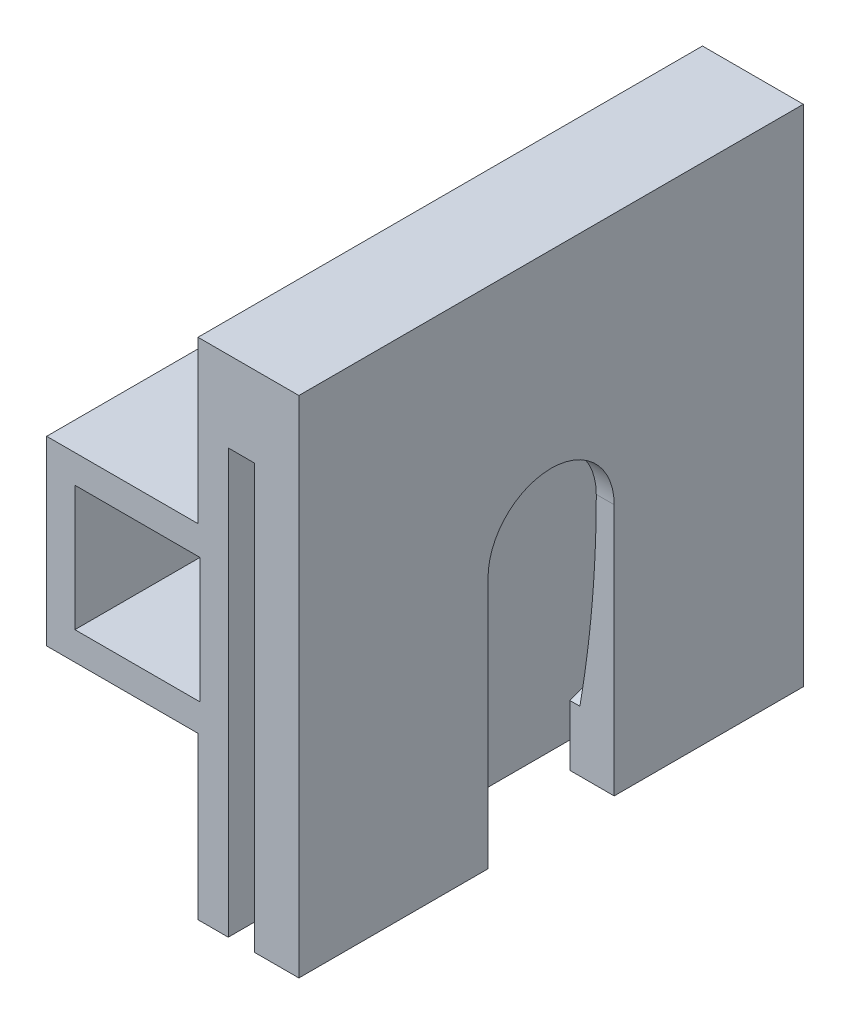
SolidWorks part; units mm, degrees
ref_plane "Plan de face" through (0, 0, 0) normal (0, 0, 1) x (1, 0, 0)
ref_plane "Plan de dessus" through (0, 0, 0) normal (0, 1, 0) x (1, 0, 0)
ref_plane "Plan de droite" through (0, 0, 0) normal (1, 0, 0) x (0, 0, -1)
sketch "Sketch1" plane through (0, 0, 0) normal (0, 0, 1) x (1, 0, 0)
  line L1 (4.5, 4.5) -> (-4.5, 4.5)
  line L2 (4.5, 4.5) -> (4.5, -4.5)
  line L3 (4.5, -4.5) -> (-4.5, -4.5)
  line L4 (-4.5, 4.5) -> (-4.5, -4.5)
  line L5 (4.5, 4.5) -> (-4.5, -4.5) construction
  line L6 (4.5, -4.5) -> (-4.5, 4.5) construction
  point P0 (0, 0)
  dimension "D1" = 9
extrude "Boss-Extrude1" add sketch "Sketch1" along normal blind 25
sketch "Sketch2" plane through (0, 0, 0) normal (0, 0, -1) x (-1, 0, 0)
  line L1 (3, 3) -> (-3, 3)
  line L2 (3, 3) -> (3, -3)
  line L3 (3, -3) -> (-3, -3)
  line L4 (-3, 3) -> (-3, -3)
  line L5 (3, 3) -> (-3, -3) construction
  line L6 (3, -3) -> (-3, 3) construction
  point P0 (0, 0)
  dimension "D1" = 6
extrude "Cut-Extrude1" cut sketch "Sketch2" against normal through all
sketch "Sketch4" plane through (4.5, 0, 0) normal (1, 0, 0) x (0, 0, -1)
  line L0 (-25, -4.5) -> (-25, 4.5) construction
  line L1 (-25, 12.5) -> (0, 12.5)
  line L2 (-25, 12.5) -> (-25, -12.5)
  line L3 (-25, -12.5) -> (0, -12.5)
  line L4 (0, 12.5) -> (0, -12.5)
  line L5 (0, -4.5) -> (0, 4.5) construction
  line L6 (-25, 12.5) -> (0, 4.5) construction
  line L7 (0, -4.5) -> (-25, -12.5) construction
extrude "Boss-Extrude2" add sketch "Sketch4" against normal up to surface (1.5 mm away) up to face at (3, 0, 12.5)
ref_plane "Plane1" through (4.5, 0, 0) normal (1, 0, 0) x (0, 0, -1)
ref_plane "Plane2" through (0, 0, 12.5) normal (0, 0, -1) x (-1, 0, 0)
ref_plane "Plane3" through (0, 0, 0) normal (0, 1, 0) x (1, 0, 0)
ref_axis "Axis1" through (4.575, 0, 12.5) along (-1, 0, 0)
sketch "Sketch5" plane through (4.5, 0, 0) normal (1, 0, 0) x (0, 0, -1)
  line L4 (0, -12.5) -> (0, 12.5)
  line L5 (0, 12.5) -> (-25, 12.5)
  line L6 (-25, 12.5) -> (-25, -12.5)
  line L7 (-25, -12.5) -> (0, -12.5)
  line L8 (0, -12.5) -> (0, 12.5)
  line L9 (0, 12.5) -> (-25, 12.5)
  line L10 (-25, 12.5) -> (-25, -12.5)
  line L11 (-25, -12.5) -> (0, -12.5)
  dimension "D1" = 0
extrude "Boss-Extrude3" add sketch "Sketch5" along normal blind 3.5
sketch "Sketch6" plane through (0, 0, 12.5) normal (0, 0, -1) x (-1, 0, 0)
  line L0 (-4.5, 10) -> (-4.5, 0)
  line L1 (-4.5, 13.75) -> (-4.5, -13.75) construction
  line L2 (-4.5, 10) -> (-6.3, 10)
  line L3 (-6.3, 10) -> (-6.3, 0) construction
  line L4 (0.825, 0) -> (-0.825, 0) construction
  line L5 (-8, 12.5) -> (-8, -12.5) construction
  line L6 (-8, 12.5) -> (-8, -12.5) construction
  line L7 (-8, 12.5) -> (-6.3, 10) construction
  line L9 (-4.5, 0) -> (-7.1999, 0)
  arc A0 (-6.3, 10) -> (-7.1999, 0) centre (48.81, 0) ccw
  dimension "D3" = 55.11
  dimension "D1" = 1.8
  dimension "D2" = 10
revolve "Cut-Revolve2" cut sketch "Sketch6" angle 360 about axis through (4.575, 0, 12.5) along (-1, 0, 0)
sketch "Sketch7" plane through (0, -12.5, 0) normal (0, -1, 0) x (1, 0, 0)
  line L0 (3, 25) -> (8, 25) construction
  line L1 (4.5, 25) -> (6.3, 25)
  line L2 (4.5, 25) -> (4.5, 0)
  line L3 (4.5, 0) -> (6.3, 0)
  line L4 (6.3, 25) -> (6.3, 0)
  line L5 (3, 0) -> (8, 0) construction
  line L6 (4.5, 2.5) -> (4.5, 22.5) construction
  line L7 (6.3, 2.5) -> (6.3, 22.5) construction
extrude "Cut-Extrude5" cut sketch "Sketch7" against normal blind 21
sketch "Sketch8" plane through (8, 0, 0) normal (1, 0, 0) x (0, 0, -1)
  line L0 (-12.5, 0) -> (-12.5, -12.5) construction
  line L1 (-9.375, 0) -> (-9.375, -12.5)
  line L2 (-15.625, 0) -> (-15.625, -12.5)
  line L3 (-12.5, -4.95) -> (-12.5, 4.95) construction
  line L4 (0.825, 0) -> (-0.825, 0) construction
  line L5 (-25, -12.5) -> (0, -12.5) construction
  arc A0 (-9.375, 0) -> (-15.625, 0) centre (-12.5, 0) ccw
  arc A1 (-15.625, -12.5) -> (-9.375, -12.5) centre (-12.5, -12.5) ccw
  point P2 (-12.5, -6.25)
  dimension "D1" = 6.25
extrude "Cut-Extrude6" cut sketch "Sketch8" against normal up to surface (1.7 mm away)
sketch "Sketch9" plane through (6.3, 0, 0) normal (-1, 0, 0) x (0, 0, 1)
  line L0 (15.625, -9.4992) -> (15.625, -12.5) construction
  line L1 (15.625, -12.5) -> (25, -12.5) construction
  line L2 (25, -12.5) -> (25, 8.5) construction
  line L3 (25, 8.5) -> (17.7678, 8.5) construction
  line L4 (0, -12.5) -> (9.375, -12.5) construction
  line L5 (9.375, -12.5) -> (9.375, -9.4992) construction
  line L6 (7.2322, 8.5) -> (0, 8.5) construction
  line L7 (0, 8.5) -> (0, -12.5) construction
  line L8 (15.625, -9.4992) -> (15.625, -12.5)
  line L9 (15.625, -12.5) -> (25, -12.5)
  line L10 (25, -12.5) -> (25, 8.5)
  line L11 (25, 8.5) -> (17.7678, 8.5)
  line L12 (0, -12.5) -> (9.375, -12.5)
  line L13 (9.375, -12.5) -> (9.375, -9.4992)
  line L14 (7.2322, 8.5) -> (0, 8.5)
  line L15 (0, 8.5) -> (0, -12.5)
  arc A0 (15.625, -9.4992) -> (17.7678, 8.5) centre (12.5, 0) ccw construction
  arc A1 (7.2322, 8.5) -> (9.375, -9.4992) centre (12.5, 0) ccw construction
  arc A2 (15.625, -9.4992) -> (17.7678, 8.5) centre (12.5, 0) ccw
  arc A3 (7.2322, 8.5) -> (9.375, -9.4992) centre (12.5, 0) ccw
extrude "Boss-Extrude4" add sketch "Sketch9" along normal blind 0.5
sketch "Sketch10" plane through (0, 0, 0) normal (0, 0, -1) x (-1, 0, 0)
  line L0 (3, 3) -> (-3, 3) construction
  line L1 (3.1, -3.1) -> (-3.1, -3.1)
  line L2 (3.1, -3.1) -> (3.1, 3.1)
  line L3 (3.1, 3.1) -> (-3.1, 3.1)
  line L4 (-3.1, -3.1) -> (-3.1, 3.1)
  line L5 (3.1, -3.1) -> (-3.1, 3.1) construction
  line L6 (3.1, 3.1) -> (-3.1, -3.1) construction
  point P0 (0, 0)
  dimension "D1" = 0.1
extrude "Cut-Extrude8" cut sketch "Sketch10" against normal through all
